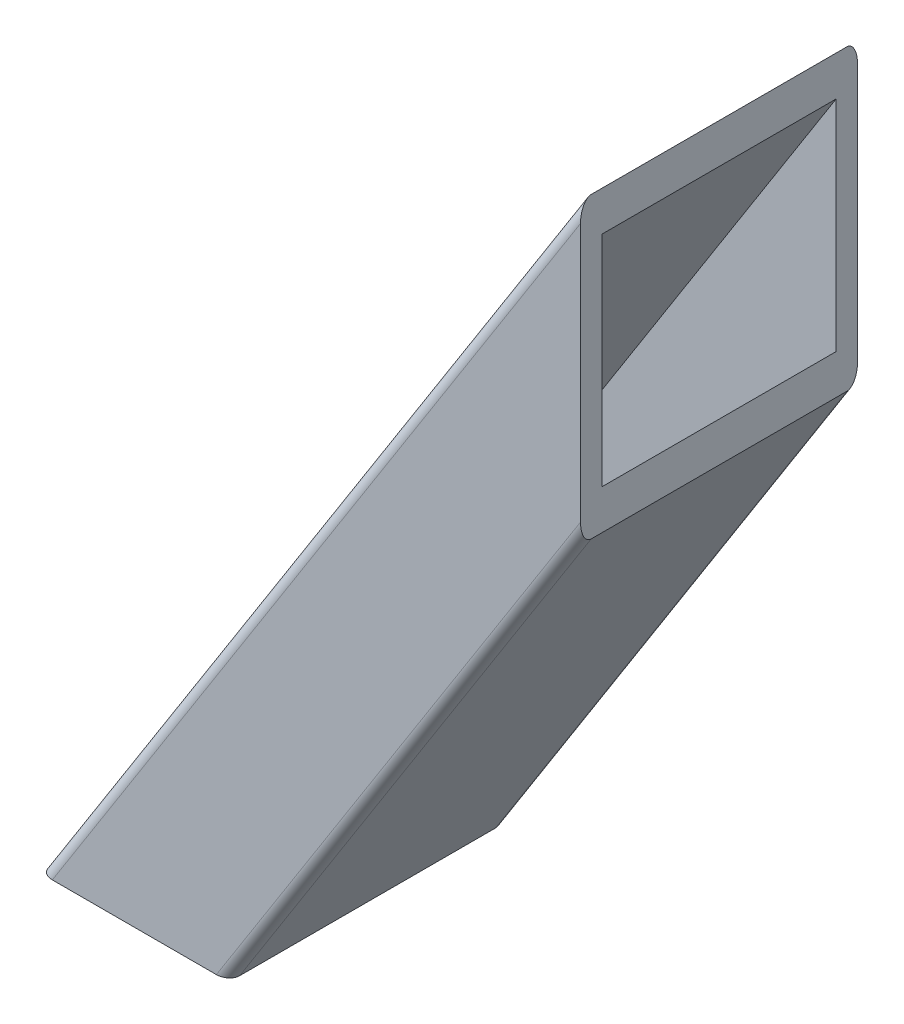
SolidWorks part; units mm, degrees
ref_plane "Front Plane" through (0, 0, 0) normal (0, 0, 1) x (1, 0, 0)
ref_plane "Top Plane" through (0, 0, 0) normal (0, 1, 0) x (1, 0, 0)
ref_plane "Right Plane" through (0, 0, 0) normal (1, 0, 0) x (0, 0, -1)
sketch "Sketch1" plane through (0, 0, 0) normal (0, 0, 1) x (1, 0, 0)
  line L0 (0, 0) -> (-17.7641, 0)
  line L1 (32.9905, 80) -> (32.9905, 52)
  line L2 (0, 0) -> (32.9905, 52)
  line L3 (-17.7641, 0) -> (32.9905, 80)
  line L5 (14.3, 0) -> (-14.3, 0) construction
  dimension "D1" = 80
  dimension "D2" = 15
  dimension "D4" = 28
extrude "Boss-Extrude1" add sketch "Sketch1" along normal blind 26
shell "Shell1" thickness 2
sketch "Sketch2" plane through (0, 2, 0) normal (0, 1, 0) x (1, 0, 0)
  line L0 (-1.0997, -2) -> (-1.0997, -24)
  line L1 (-1.0997, -24) -> (-14.1267, -24)
  line L2 (-14.1267, -24) -> (-14.1267, -2)
  line L3 (-14.1267, -2) -> (-1.0997, -2)
extrude "Cut-Extrude1" cut sketch "Sketch2" against normal up to next
fillet "Fillet1" radius 1 4 edges at (16.4952, 26, 0) (7.6132, 40, 0) (16.4952, 26, 26) (7.6132, 40, 26)
